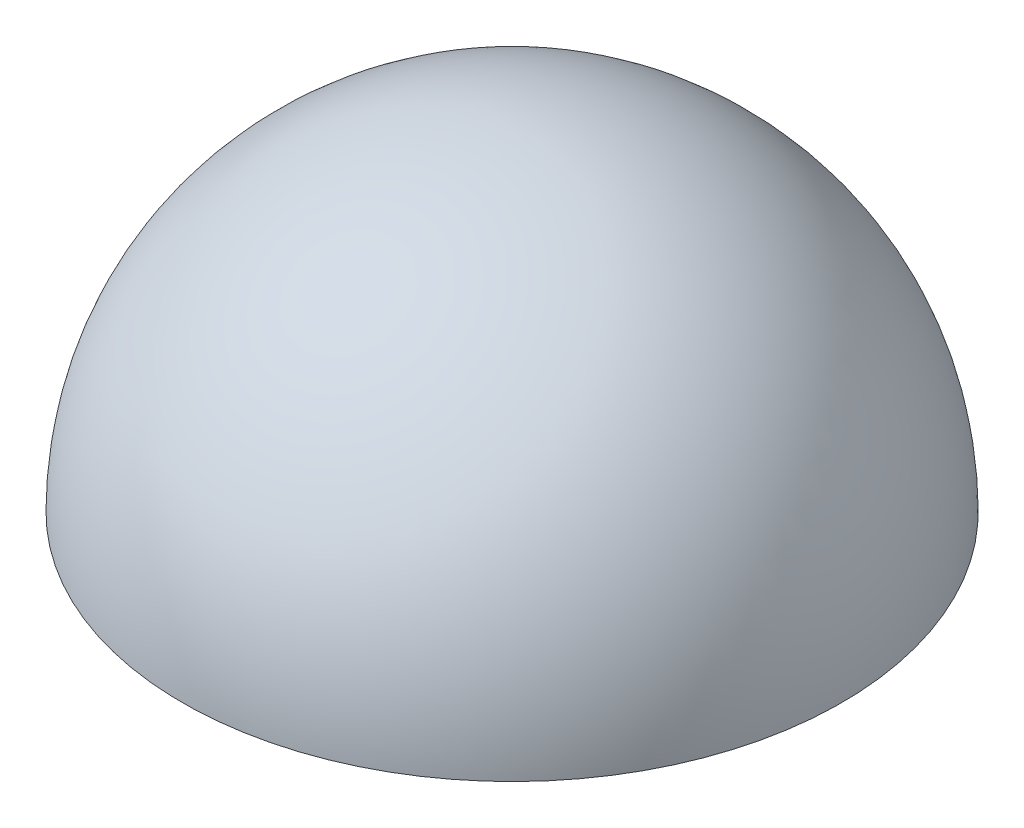
SolidWorks part; units mm, degrees
ref_plane "Front Plane" through (0, 0, 0) normal (0, 0, 1) x (1, 0, 0)
ref_plane "Top Plane" through (0, 0, 0) normal (0, 1, 0) x (1, 0, 0)
ref_plane "Right Plane" through (0, 0, 0) normal (1, 0, 0) x (0, 0, -1)
sketch "Sketch1" plane through (0, 0, 0) normal (0, 1, 0) x (1, 0, 0)
  line L0 (-47.1862, 0) -> (46.7474, 0) construction
  line L1 (-33.5, 0) -> (33.5, 0)
  arc A0 (33.5, 0) -> (-33.5, 0) centre (0, 0) ccw
  dimension "D1" = 67
revolve "Revolve1" add sketch "Sketch1" angle 180 about L0
